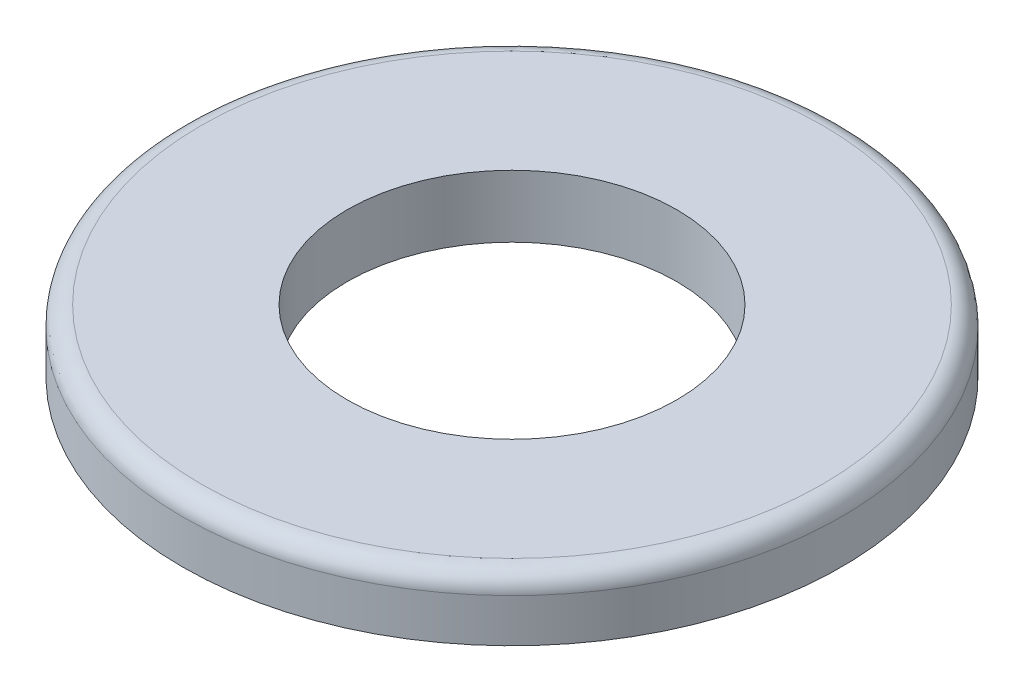
SolidWorks part; units mm, degrees
ref_plane "Front Plane" through (0, 0, 0) normal (0, 0, 1) x (1, 0, 0)
ref_plane "Top Plane" through (0, 0, 0) normal (0, 1, 0) x (1, 0, 0)
ref_plane "Right Plane" through (0, 0, 0) normal (1, 0, 0) x (0, 0, -1)
sketch "Sketch1" plane through (0, 0, 0) normal (0, 1, 0) x (1, 0, 0)
  circle A0 centre (0, 0) radius 8.7312
  circle A1 centre (0, 0) radius 4.3656
  dimension "D1" = 8.7312
  dimension "D2" = 17.4625
extrude "Boss-Extrude1" add sketch "Sketch1" along normal blind 1.651
fillet "Fillet1" radius 0.5 1 edges at (0, 1.651, 8.7312)
